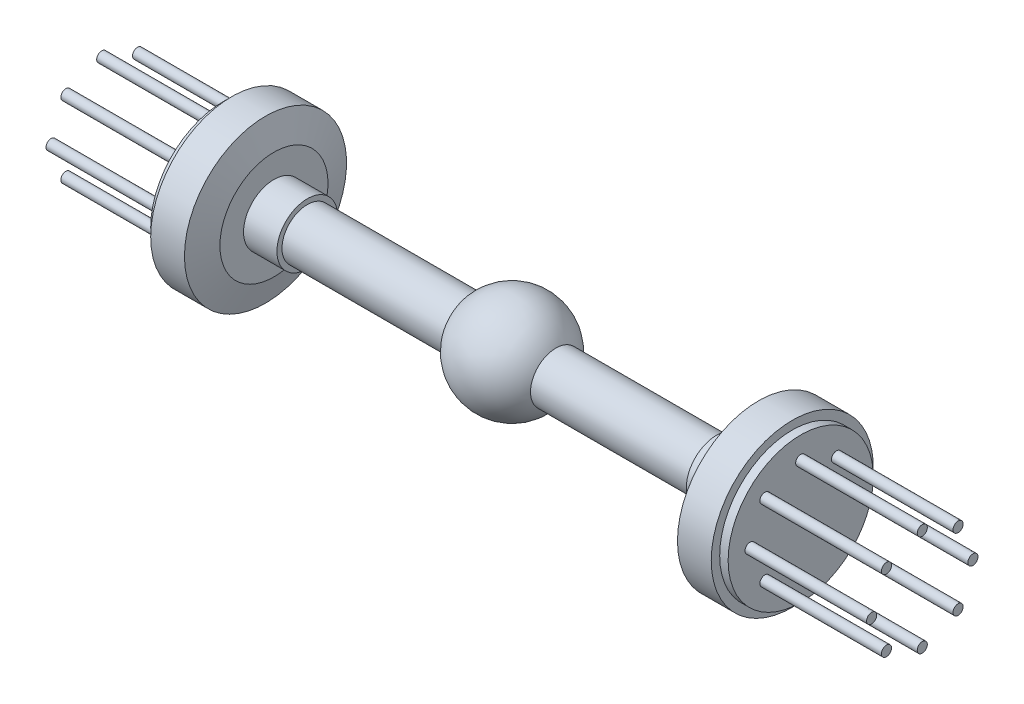
SolidWorks part; units mm, degrees
ref_plane "Front Plane" through (0, 0, 0) normal (0, 0, 1) x (1, 0, 0)
ref_plane "Top Plane" through (0, 0, 0) normal (0, 1, 0) x (1, 0, 0)
ref_plane "Right Plane" through (0, 0, 0) normal (1, 0, 0) x (0, 0, -1)
sketch "Sketch1" plane through (0, 0, 0) normal (0, 0, 1) x (1, 0, 0)
  line L0 (-1250, 0) -> (1250, 0) construction
  line L1 (-855, 0) -> (-855, 215)
  line L2 (-855, 215) -> (-830, 215)
  line L3 (-830, 215) -> (-830, 240)
  line L4 (-830, 240) -> (-730, 240)
  line L5 (-730, 240) -> (-705, 160)
  line L6 (-705, 160) -> (-705, 90)
  line L7 (-705, 90) -> (-606.1562, 90)
  line L8 (-606.1562, 90) -> (-606.1562, 75)
  line L9 (-606.1562, 75) -> (-129.9038, 75)
  line L10 (-855, 0) -> (855, 0)
  line L11 (606.1562, 75) -> (129.9038, 75)
  line L12 (606.1562, 90) -> (606.1562, 75)
  line L13 (705, 90) -> (606.1562, 90)
  line L14 (705, 160) -> (705, 90)
  line L15 (730, 240) -> (705, 160)
  line L16 (830, 240) -> (730, 240)
  line L17 (830, 215) -> (830, 240)
  line L18 (855, 215) -> (830, 215)
  line L19 (855, 0) -> (855, 215)
  arc A0 (129.9038, 75) -> (-129.9038, 75) centre (0, 0) ccw
  dimension "D6" = 300
  dimension "D12" = 150
  dimension "D1" = 2500
  dimension "D2" = 215
  dimension "D3" = 25
  dimension "D4" = 100
  dimension "D5" = 395
  dimension "D7" = 75
  dimension "D8" = 25
  dimension "D9" = 25
  dimension "D10" = 15
  dimension "D11" = 70
revolve "Revolve1" add sketch "Sketch1" angle 360 about L0
sketch "Sketch2" plane through (-855, 0, 0) normal (-1, 0, 0) x (0, 0, 1)
  circle A0 centre (0, 150) radius 15
  circle A1 centre (106.066, 106.066) radius 15
  circle A2 centre (150, 0) radius 15
  circle A3 centre (106.066, -106.066) radius 15
  circle A4 centre (0, -150) radius 15
  circle A5 centre (-106.066, -106.066) radius 15
  circle A6 centre (-150, 0) radius 15
  circle A7 centre (-106.066, 106.066) radius 15
  dimension "D1" = 30
  dimension "D2" = 150
  dimension "D3" = 8
extrude "Boss-Extrude1" add sketch "Sketch2" along normal blind 360
mirror "Mirror1" about plane through (0, 0, 0) normal (1, 0, 0) of "Boss-Extrude1"
